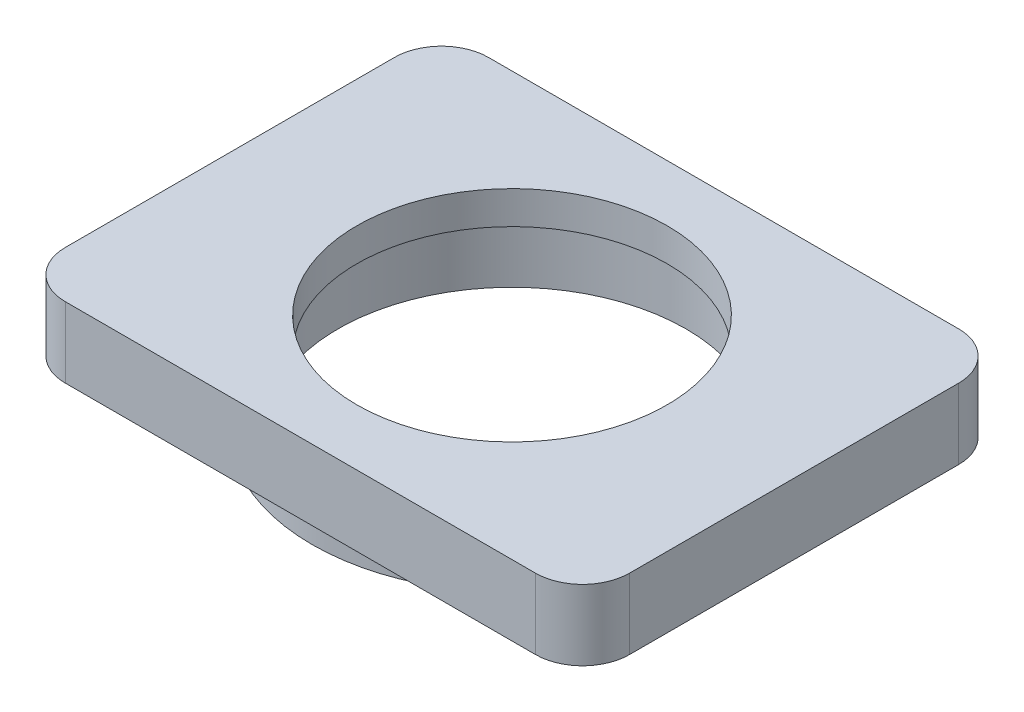
SolidWorks part; units mm, degrees
ref_plane "Front Plane" through (0, 0, 0) normal (0, 0, 1) x (1, 0, 0)
ref_plane "Top Plane" through (0, 0, 0) normal (0, 1, 0) x (1, 0, 0)
ref_plane "Right Plane" through (0, 0, 0) normal (1, 0, 0) x (0, 0, -1)
sketch "Sketch1" plane through (0, 0, 0) normal (0, 1, 0) x (1, 0, 0)
  circle A4 centre (0, 0) radius 18.5
  circle A5 centre (0, 0) radius 21.25
  dimension "D1" = 37
  dimension "D2" = 42.5
extrude "Boss-Extrude1" add sketch "Sketch1" along normal blind 8
sketch "Sketch2" plane through (0, 8, 0) normal (0, 1, 0) x (1, 0, 0)
  circle A0 centre (0, 0) radius 22.5
  circle A1 centre (0, 0) radius 16.5
  dimension "D1" = 45
  dimension "D2" = 33
extrude "Boss-Extrude2" add sketch "Sketch2" along normal blind 2.5
sketch "Sketch3" plane through (0, 10.5, 0) normal (0, 1, 0) x (1, 0, 0)
  line L1 (-30, -22.5) -> (30, -22.5)
  line L2 (-30, -22.5) -> (-30, 22.5)
  line L3 (-30, 22.5) -> (30, 22.5)
  line L4 (30, -22.5) -> (30, 22.5)
  line L5 (-30, -22.5) -> (30, 22.5) construction
  line L6 (-30, 22.5) -> (30, -22.5) construction
  circle A0 centre (0, 0) radius 16.5
  circle A1 centre (0, 0) radius 16.5 construction
  point P0 (0, 0)
  dimension "D3" = 0
  dimension "D1" = 60
  dimension "D2" = 45
extrude "Boss-Extrude3" add sketch "Sketch3" against normal blind 7.5
fillet "Fillet2" radius 5 4 edges at (30, 6.75, -22.5) (30, 6.75, 22.5) (-30, 6.75, 22.5) (-30, 6.75, -22.5)
sketch "Sketch4" plane through (0, 3, 0) normal (0, -1, 0) x (-1, 0, 0)
  circle A0 centre (0, 0) radius 18.5
extrude "Cut-Extrude1" cut sketch "Sketch4" against normal blind 4
sketch "Sketch5" plane through (0, 3, 0) normal (0, -1, 0) x (-1, 0, 0)
  circle A0 centre (25, -17.5) radius 1.75
  circle A1 centre (-25, -17.5) radius 1.75
  circle A2 centre (-25, 17.5) radius 1.75
  circle A3 centre (25, 17.5) radius 1.75
  dimension "D1" = 3.5
extrude "Cut-Extrude2" cut sketch "Sketch5" against normal blind 6.2
